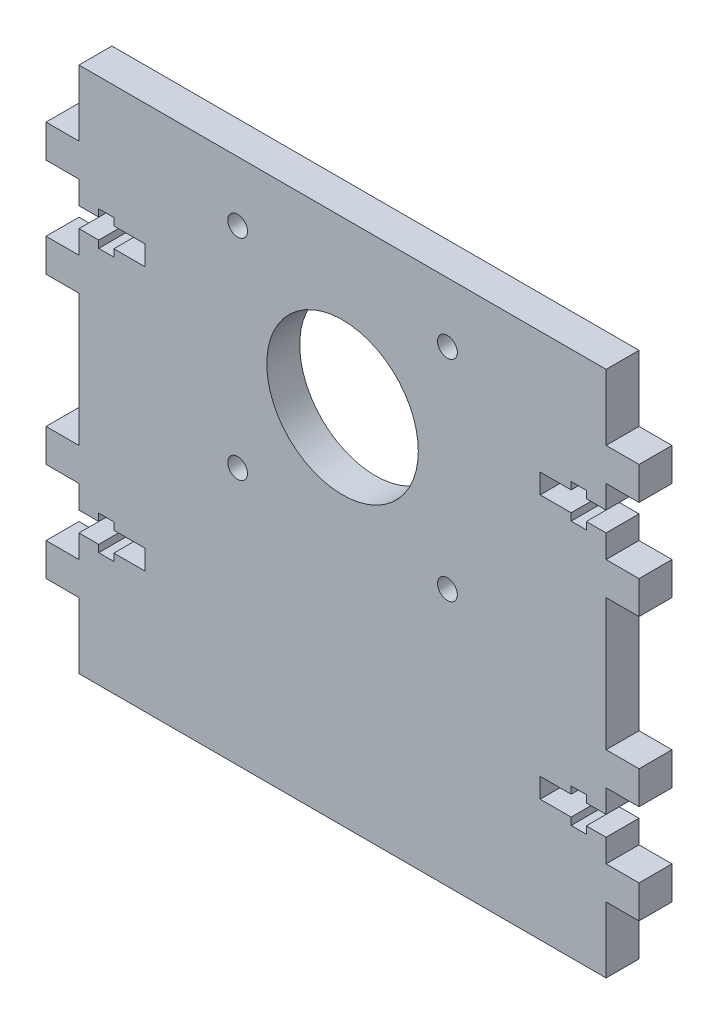
SolidWorks part; units mm, degrees
ref_plane "Front Plane" through (0, 0, 0) normal (0, 0, 1) x (1, 0, 0)
ref_plane "Top Plane" through (0, 0, 0) normal (0, 1, 0) x (1, 0, 0)
ref_plane "Right Plane" through (0, 0, 0) normal (1, 0, 0) x (0, 0, -1)
sketch "Sketch1" plane through (0, 0, 0) normal (0, 0, 1) x (1, 0, 0)
  line L0 (0, 0) -> (0, 80) construction
  line L1 (0, 80) -> (-80, 80)
  line L4 (-40, 80) -> (-40, 0) construction
  line L5 (0, 40) -> (-80, 40) construction
  line L6 (0, 60) -> (-11.2208, 60) construction
  line L7 (0, 58.5) -> (0, 55)
  line L8 (5, 55) -> (5, 50)
  line L9 (5, 50) -> (0, 50)
  line L10 (5, 55) -> (0, 55)
  line L11 (0, 61.5) -> (0, 65)
  line L12 (0, 65) -> (5, 65)
  line L13 (5, 65) -> (5, 70)
  line L14 (5, 70) -> (0, 70)
  line L15 (0, 58.5) -> (0, 61.5) construction
  line L16 (0, 61.5) -> (-3, 61.5)
  line L17 (-5.3, 61.5) -> (-5.3, 62.6)
  line L18 (-3, 57.4) -> (-5.3, 57.4)
  line L19 (-3, 62.6) -> (-3, 61.5)
  line L20 (-5.3, 61.5) -> (-10, 61.5)
  line L21 (-10, 61.5) -> (-10, 58.5)
  line L22 (-10, 58.5) -> (-5.3, 58.5)
  line L23 (-3, 58.5) -> (-3, 57.4)
  line L24 (-5.3, 62.6) -> (-3, 62.6)
  line L25 (-5.3, 57.4) -> (-5.3, 58.5)
  line L26 (-3, 58.5) -> (0, 58.5)
  line L27 (-10, 60) -> (0, 60) construction
  line L66 (-85, 70) -> (-80, 70)
  line L67 (-85, 65) -> (-85, 70)
  line L68 (-80, 65) -> (-85, 65)
  line L69 (-80, 61.5) -> (-80, 65)
  line L70 (-80, 61.5) -> (-77, 61.5)
  line L71 (-77, 62.6) -> (-77, 61.5)
  line L72 (-74.7, 62.6) -> (-77, 62.6)
  line L73 (-74.7, 61.5) -> (-74.7, 62.6)
  line L74 (-74.7, 61.5) -> (-70, 61.5)
  line L75 (-70, 61.5) -> (-70, 58.5)
  line L76 (-70, 58.5) -> (-74.7, 58.5)
  line L77 (-74.7, 57.4) -> (-74.7, 58.5)
  line L78 (-77, 57.4) -> (-74.7, 57.4)
  line L79 (-77, 58.5) -> (-77, 57.4)
  line L80 (-77, 58.5) -> (-80, 58.5)
  line L81 (-80, 58.5) -> (-80, 55)
  line L82 (-85, 55) -> (-80, 55)
  line L83 (-85, 55) -> (-85, 50)
  line L84 (-85, 50) -> (-80, 50)
  line L85 (-80, 80) -> (-80, 70)
  line L90 (0, 70) -> (0, 80)
  line L91 (-85, 30) -> (-80, 30)
  line L92 (-85, 25) -> (-85, 30)
  line L93 (-85, 25) -> (-80, 25)
  line L94 (-80, 21.5) -> (-80, 25)
  line L95 (-77, 21.5) -> (-80, 21.5)
  line L96 (-77, 21.5) -> (-77, 22.6)
  line L97 (-77, 22.6) -> (-74.7, 22.6)
  line L98 (-74.7, 22.6) -> (-74.7, 21.5)
  line L99 (-70, 21.5) -> (-74.7, 21.5)
  line L100 (-70, 18.5) -> (-70, 21.5)
  line L101 (-74.7, 18.5) -> (-70, 18.5)
  line L102 (-74.7, 18.5) -> (-74.7, 17.4)
  line L103 (-74.7, 17.4) -> (-77, 17.4)
  line L104 (-77, 17.4) -> (-77, 18.5)
  line L105 (-80, 18.5) -> (-77, 18.5)
  line L106 (-80, 18.5) -> (-80, 15)
  line L107 (-80, 15) -> (-85, 15)
  line L108 (-85, 15) -> (-85, 10)
  line L109 (-85, 10) -> (-80, 10)
  line L110 (-80, 0) -> (-80, 10)
  line L111 (0, 0) -> (-80, 0)
  line L112 (0, 10) -> (0, 0)
  line L113 (5, 10) -> (0, 10)
  line L114 (5, 15) -> (5, 10)
  line L115 (0, 15) -> (5, 15)
  line L116 (0, 18.5) -> (0, 15)
  line L117 (0, 18.5) -> (-3, 18.5)
  line L118 (-3, 17.4) -> (-3, 18.5)
  line L119 (-5.3, 17.4) -> (-3, 17.4)
  line L120 (-5.3, 18.5) -> (-5.3, 17.4)
  line L121 (-5.3, 18.5) -> (-10, 18.5)
  line L122 (-10, 18.5) -> (-10, 21.5)
  line L123 (-10, 21.5) -> (-5.3, 21.5)
  line L124 (-5.3, 22.6) -> (-5.3, 21.5)
  line L125 (-3, 22.6) -> (-5.3, 22.6)
  line L126 (-3, 21.5) -> (-3, 22.6)
  line L127 (-3, 21.5) -> (0, 21.5)
  line L128 (0, 21.5) -> (0, 25)
  line L129 (5, 25) -> (0, 25)
  line L130 (5, 25) -> (5, 30)
  line L131 (5, 30) -> (0, 30)
  line L132 (-80, 50) -> (-80, 30)
  line L133 (0, 50) -> (0, 30)
  circle B0 centre (-55.922, 70.922) radius 1.5
  circle B1 centre (-24.078, 70.922) radius 1.5
  circle B2 centre (-24.078, 39.078) radius 1.5
  circle B3 centre (-55.922, 39.078) radius 1.5
  circle B4 centre (-40, 55) radius 11.5
  dimension "D2" = 40
  dimension "D3" = 80
  dimension "D4" = 10
  dimension "D5" = 5
  dimension "D6" = 5
  dimension "D7" = 5.2
  dimension "D8" = 3
  dimension "D9" = 2.3
  dimension "D10" = 3
  dimension "D11" = 10
  dimension "D12" = 15
sketch_block_instance "Fixation Nema 17-1"
sketch_block "Fixation Nema 17"
extrude "Boss-Extrude1" add sketch "Sketch1" along normal blind 5
